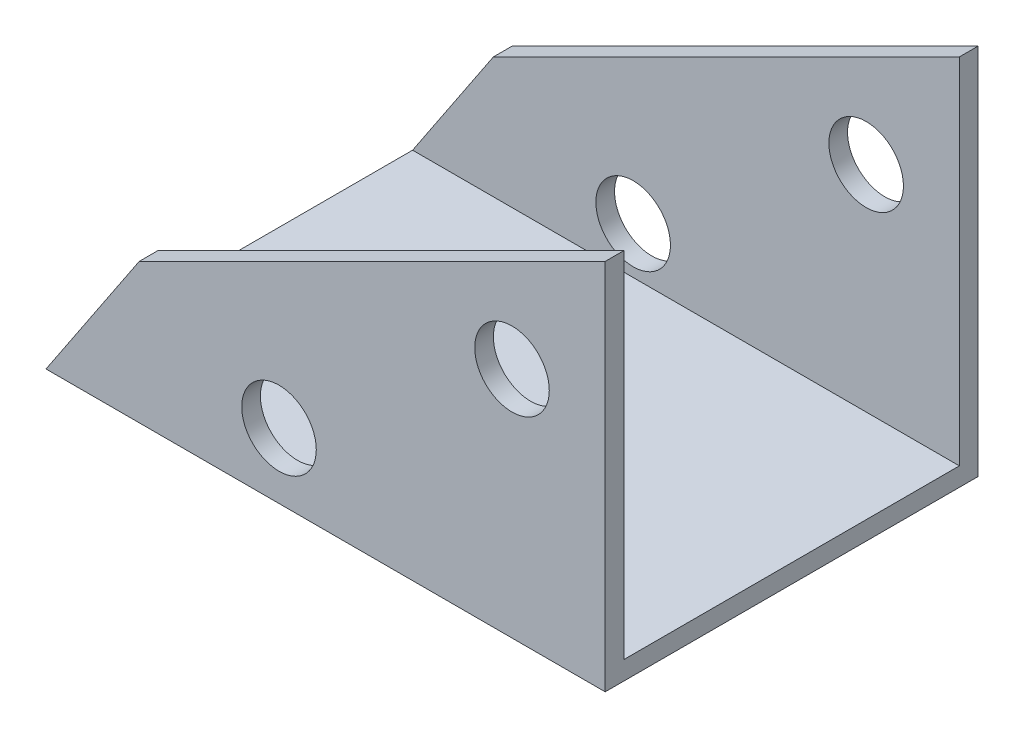
SolidWorks part; units mm, degrees
ref_plane "Front Plane" through (0, 0, 0) normal (0, 0, 1) x (1, 0, 0)
ref_plane "Top Plane" through (0, 0, 0) normal (0, 1, 0) x (1, 0, 0)
ref_plane "Right Plane" through (0, 0, 0) normal (1, 0, 0) x (0, 0, -1)
sketch "Sketch1" plane through (0, 0, 0) normal (0, 1, 0) x (1, 0, 0)
  line L1 (0, 0) -> (60, 0)
  line L2 (0, 0) -> (0, 40)
  line L3 (0, 40) -> (60, 40)
  line L4 (60, 0) -> (60, 40)
  dimension "D1" = 60
  dimension "D2" = 40
extrude "Boss-Extrude1" add sketch "Sketch1" along normal blind 40
sketch "Sketch5" plane through (60, 0, 0) normal (1, 0, 0) x (0, 0, -1)
  line L0 (0, 40) -> (40, 40) construction
  line L1 (2, 2) -> (38, 2)
  line L2 (2, 2) -> (2, 40)
  line L3 (2, 40) -> (38, 40)
  line L4 (38, 2) -> (38, 40)
  line L5 (0, 40) -> (0, 0) construction
  line L6 (0, 0) -> (40, 0) construction
  line L7 (40, 40) -> (40, 0) construction
  point P8 (0, 20)
  point P11 (20, 0)
  point P14 (40, 20)
  dimension "D1" = 2
  dimension "D2" = 2
  dimension "D3" = 2
extrude "Cut-Extrude3" cut sketch "Sketch5" against normal through all
sketch "Sketch6" plane through (0, 0, 0) normal (0, 0, 1) x (1, 0, 0)
  line L0 (0, 40) -> (0, 0) construction
  line L1 (0, 0) -> (60, 0) construction
  line L2 (60, 40) -> (60, 0) construction
  line L3 (60, 40) -> (10, 15)
  line L4 (10, 15) -> (0, 0)
  circle A0 centre (25, 7) radius 4
  circle A1 centre (50, 25) radius 4
  point P10 (10, 15)
  line M4 (60, 40) -> (0, 40)
  line M5 (0, 40) -> (0, 0)
  dimension "D1" = 8
  dimension "D4" = 8
  dimension "D2" = 25
  dimension "D3" = 7
  dimension "D5" = 10
  dimension "D6" = 25
extrude "Cut-Extrude4" cut sketch "Sketch6" against normal through all contours L4 L3 M4 M5 | A0 | A1
